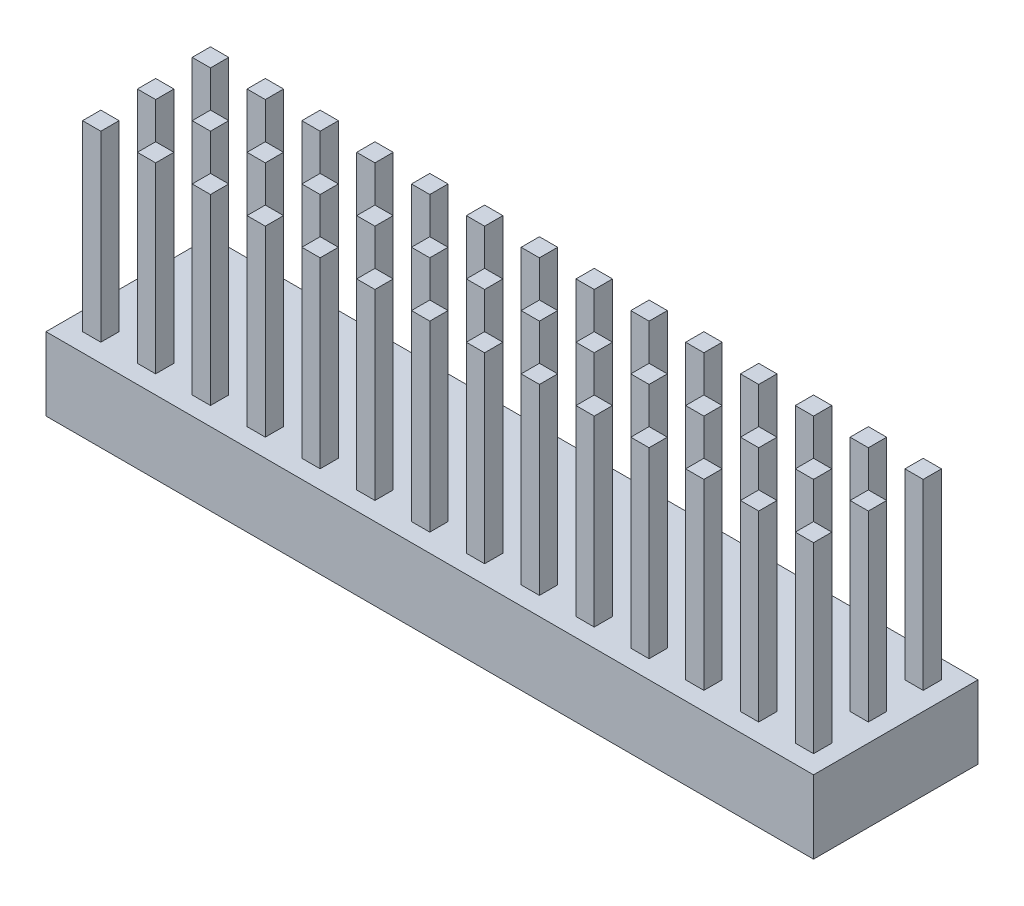
SolidWorks part; units mm, degrees
ref_plane "Front Plane" through (0, 0, 0) normal (0, 0, 1) x (1, 0, 0)
ref_plane "Top Plane" through (0, 0, 0) normal (0, 1, 0) x (1, 0, 0)
ref_plane "Right Plane" through (0, 0, 0) normal (1, 0, 0) x (0, 0, -1)
sketch "Sketch1" plane through (0, 0, 0) normal (0, 1, 0) x (1, 0, 0)
  line L1 (0, 0) -> (32.004, 0)
  line L2 (0, 0) -> (0, 6.858)
  line L3 (0, 6.858) -> (32.004, 6.858)
  line L4 (32.004, 0) -> (32.004, 6.858)
  dimension "D1" = 32.004
  dimension "D2" = 6.858
extrude "Extrude1" add sketch "Sketch1" along normal blind 3.048
sketch "Sketch2" plane through (0, 3.048, 0) normal (0, 1, 0) x (1, 0, 0)
  line L0 (0, 6.858) -> (0, 0) construction
  line L1 (3.048, 5.334) -> (3.81, 5.334)
  line L2 (3.048, 5.334) -> (3.048, 6.096)
  line L3 (3.048, 6.096) -> (3.81, 6.096)
  line L4 (3.81, 5.334) -> (3.81, 6.096)
  line L5 (0.762, 5.334) -> (1.524, 5.334)
  line L6 (0.762, 5.334) -> (0.762, 6.096)
  line L7 (0.762, 6.096) -> (1.524, 6.096)
  line L8 (1.524, 5.334) -> (1.524, 6.096)
  line L10 (32.004, 6.858) -> (0, 6.858) construction
  line L11 (5.334, 5.334) -> (6.096, 5.334)
  line L12 (5.334, 5.334) -> (5.334, 6.096)
  line L13 (5.334, 6.096) -> (6.096, 6.096)
  line L14 (6.096, 5.334) -> (6.096, 6.096)
  line L15 (7.62, 5.334) -> (8.382, 5.334)
  line L16 (7.62, 5.334) -> (7.62, 6.096)
  line L17 (7.62, 6.096) -> (8.382, 6.096)
  line L18 (8.382, 5.334) -> (8.382, 6.096)
  line L19 (9.906, 5.334) -> (10.668, 5.334)
  line L20 (9.906, 5.334) -> (9.906, 6.096)
  line L21 (9.906, 6.096) -> (10.668, 6.096)
  line L22 (10.668, 5.334) -> (10.668, 6.096)
  line L23 (12.192, 5.334) -> (12.954, 5.334)
  line L24 (12.192, 5.334) -> (12.192, 6.096)
  line L25 (12.192, 6.096) -> (12.954, 6.096)
  line L26 (12.954, 5.334) -> (12.954, 6.096)
  line L27 (14.478, 5.334) -> (15.24, 5.334)
  line L28 (14.478, 5.334) -> (14.478, 6.096)
  line L29 (14.478, 6.096) -> (15.24, 6.096)
  line L30 (15.24, 5.334) -> (15.24, 6.096)
  line L31 (16.764, 5.334) -> (17.526, 5.334)
  line L32 (16.764, 5.334) -> (16.764, 6.096)
  line L33 (16.764, 6.096) -> (17.526, 6.096)
  line L34 (17.526, 5.334) -> (17.526, 6.096)
  line L35 (19.05, 5.334) -> (19.812, 5.334)
  line L36 (19.05, 5.334) -> (19.05, 6.096)
  line L37 (19.05, 6.096) -> (19.812, 6.096)
  line L38 (19.812, 5.334) -> (19.812, 6.096)
  line L39 (21.336, 5.334) -> (22.098, 5.334)
  line L40 (21.336, 5.334) -> (21.336, 6.096)
  line L41 (21.336, 6.096) -> (22.098, 6.096)
  line L42 (22.098, 5.334) -> (22.098, 6.096)
  line L43 (23.622, 5.334) -> (24.384, 5.334)
  line L44 (23.622, 5.334) -> (23.622, 6.096)
  line L45 (23.622, 6.096) -> (24.384, 6.096)
  line L46 (24.384, 5.334) -> (24.384, 6.096)
  line L47 (25.908, 5.334) -> (26.67, 5.334)
  line L48 (25.908, 5.334) -> (25.908, 6.096)
  line L49 (25.908, 6.096) -> (26.67, 6.096)
  line L50 (26.67, 5.334) -> (26.67, 6.096)
  line L51 (28.194, 5.334) -> (28.956, 5.334)
  line L52 (28.194, 5.334) -> (28.194, 6.096)
  line L53 (28.194, 6.096) -> (28.956, 6.096)
  line L54 (28.956, 5.334) -> (28.956, 6.096)
  line L55 (30.48, 5.334) -> (31.242, 5.334)
  line L56 (30.48, 5.334) -> (30.48, 6.096)
  line L57 (30.48, 6.096) -> (31.242, 6.096)
  line L58 (31.242, 5.334) -> (31.242, 6.096)
  line L59 (0.762, 3.048) -> (1.524, 3.048)
  line L60 (0.762, 3.048) -> (0.762, 3.81)
  line L61 (0.762, 3.81) -> (1.524, 3.81)
  line L62 (1.524, 3.048) -> (1.524, 3.81)
  line L63 (3.048, 3.048) -> (3.81, 3.048)
  line L64 (3.048, 3.048) -> (3.048, 3.81)
  line L65 (3.048, 3.81) -> (3.81, 3.81)
  line L66 (3.81, 3.048) -> (3.81, 3.81)
  line L67 (5.334, 3.048) -> (6.096, 3.048)
  line L68 (5.334, 3.048) -> (5.334, 3.81)
  line L69 (5.334, 3.81) -> (6.096, 3.81)
  line L70 (6.096, 3.048) -> (6.096, 3.81)
  line L71 (7.62, 3.048) -> (8.382, 3.048)
  line L72 (7.62, 3.048) -> (7.62, 3.81)
  line L73 (7.62, 3.81) -> (8.382, 3.81)
  line L74 (8.382, 3.048) -> (8.382, 3.81)
  line L75 (9.906, 3.048) -> (10.668, 3.048)
  line L76 (9.906, 3.048) -> (9.906, 3.81)
  line L77 (9.906, 3.81) -> (10.668, 3.81)
  line L78 (10.668, 3.048) -> (10.668, 3.81)
  line L79 (12.192, 3.048) -> (12.954, 3.048)
  line L80 (12.192, 3.048) -> (12.192, 3.81)
  line L81 (12.192, 3.81) -> (12.954, 3.81)
  line L82 (12.954, 3.048) -> (12.954, 3.81)
  line L83 (14.478, 3.048) -> (15.24, 3.048)
  line L84 (14.478, 3.048) -> (14.478, 3.81)
  line L85 (14.478, 3.81) -> (15.24, 3.81)
  line L86 (15.24, 3.048) -> (15.24, 3.81)
  line L87 (16.764, 3.048) -> (17.526, 3.048)
  line L88 (16.764, 3.048) -> (16.764, 3.81)
  line L89 (16.764, 3.81) -> (17.526, 3.81)
  line L90 (17.526, 3.048) -> (17.526, 3.81)
  line L91 (19.05, 3.048) -> (19.812, 3.048)
  line L92 (19.05, 3.048) -> (19.05, 3.81)
  line L93 (19.05, 3.81) -> (19.812, 3.81)
  line L94 (19.812, 3.048) -> (19.812, 3.81)
  line L95 (21.336, 3.048) -> (22.098, 3.048)
  line L96 (21.336, 3.048) -> (21.336, 3.81)
  line L97 (21.336, 3.81) -> (22.098, 3.81)
  line L98 (22.098, 3.048) -> (22.098, 3.81)
  line L99 (23.622, 3.048) -> (24.384, 3.048)
  line L100 (23.622, 3.048) -> (23.622, 3.81)
  line L101 (23.622, 3.81) -> (24.384, 3.81)
  line L102 (24.384, 3.048) -> (24.384, 3.81)
  line L103 (25.908, 3.048) -> (26.67, 3.048)
  line L104 (25.908, 3.048) -> (25.908, 3.81)
  line L105 (25.908, 3.81) -> (26.67, 3.81)
  line L106 (26.67, 3.048) -> (26.67, 3.81)
  line L107 (28.194, 3.048) -> (28.956, 3.048)
  line L108 (28.194, 3.048) -> (28.194, 3.81)
  line L109 (28.194, 3.81) -> (28.956, 3.81)
  line L110 (28.956, 3.048) -> (28.956, 3.81)
  line L111 (30.48, 3.048) -> (31.242, 3.048)
  line L112 (30.48, 3.048) -> (30.48, 3.81)
  line L113 (30.48, 3.81) -> (31.242, 3.81)
  line L114 (31.242, 3.048) -> (31.242, 3.81)
  line L115 (0.762, 0.762) -> (1.524, 0.762)
  line L116 (0.762, 0.762) -> (0.762, 1.524)
  line L117 (0.762, 1.524) -> (1.524, 1.524)
  line L118 (1.524, 0.762) -> (1.524, 1.524)
  line L119 (3.048, 0.762) -> (3.81, 0.762)
  line L120 (3.048, 0.762) -> (3.048, 1.524)
  line L121 (3.048, 1.524) -> (3.81, 1.524)
  line L122 (3.81, 0.762) -> (3.81, 1.524)
  line L123 (5.334, 0.762) -> (6.096, 0.762)
  line L124 (5.334, 0.762) -> (5.334, 1.524)
  line L125 (5.334, 1.524) -> (6.096, 1.524)
  line L126 (6.096, 0.762) -> (6.096, 1.524)
  line L127 (7.62, 0.762) -> (8.382, 0.762)
  line L128 (7.62, 0.762) -> (7.62, 1.524)
  line L129 (7.62, 1.524) -> (8.382, 1.524)
  line L130 (8.382, 0.762) -> (8.382, 1.524)
  line L131 (9.906, 0.762) -> (10.668, 0.762)
  line L132 (9.906, 0.762) -> (9.906, 1.524)
  line L133 (9.906, 1.524) -> (10.668, 1.524)
  line L134 (10.668, 0.762) -> (10.668, 1.524)
  line L135 (12.192, 0.762) -> (12.954, 0.762)
  line L136 (12.192, 0.762) -> (12.192, 1.524)
  line L137 (12.192, 1.524) -> (12.954, 1.524)
  line L138 (12.954, 0.762) -> (12.954, 1.524)
  line L139 (14.478, 0.762) -> (15.24, 0.762)
  line L140 (14.478, 0.762) -> (14.478, 1.524)
  line L141 (14.478, 1.524) -> (15.24, 1.524)
  line L142 (15.24, 0.762) -> (15.24, 1.524)
  line L143 (16.764, 0.762) -> (17.526, 0.762)
  line L144 (16.764, 0.762) -> (16.764, 1.524)
  line L145 (16.764, 1.524) -> (17.526, 1.524)
  line L146 (17.526, 0.762) -> (17.526, 1.524)
  line L147 (19.05, 0.762) -> (19.812, 0.762)
  line L148 (19.05, 0.762) -> (19.05, 1.524)
  line L149 (19.05, 1.524) -> (19.812, 1.524)
  line L150 (19.812, 0.762) -> (19.812, 1.524)
  line L151 (21.336, 0.762) -> (22.098, 0.762)
  line L152 (21.336, 0.762) -> (21.336, 1.524)
  line L153 (21.336, 1.524) -> (22.098, 1.524)
  line L154 (22.098, 0.762) -> (22.098, 1.524)
  line L155 (23.622, 0.762) -> (24.384, 0.762)
  line L156 (23.622, 0.762) -> (23.622, 1.524)
  line L157 (23.622, 1.524) -> (24.384, 1.524)
  line L158 (24.384, 0.762) -> (24.384, 1.524)
  line L159 (25.908, 0.762) -> (26.67, 0.762)
  line L160 (25.908, 0.762) -> (25.908, 1.524)
  line L161 (25.908, 1.524) -> (26.67, 1.524)
  line L162 (26.67, 0.762) -> (26.67, 1.524)
  line L163 (28.194, 0.762) -> (28.956, 0.762)
  line L164 (28.194, 0.762) -> (28.194, 1.524)
  line L165 (28.194, 1.524) -> (28.956, 1.524)
  line L166 (28.956, 0.762) -> (28.956, 1.524)
  line L167 (30.48, 0.762) -> (31.242, 0.762)
  line L168 (30.48, 0.762) -> (30.48, 1.524)
  line L169 (30.48, 1.524) -> (31.242, 1.524)
  line L170 (31.242, 0.762) -> (31.242, 1.524)
  dimension "D3" = 0.762
  dimension "D4" = 0.762
  dimension "D5" = 0.762
  dimension "D8" = 0.762
extrude "Extrude2" add sketch "Sketch2" along normal blind 7.62
